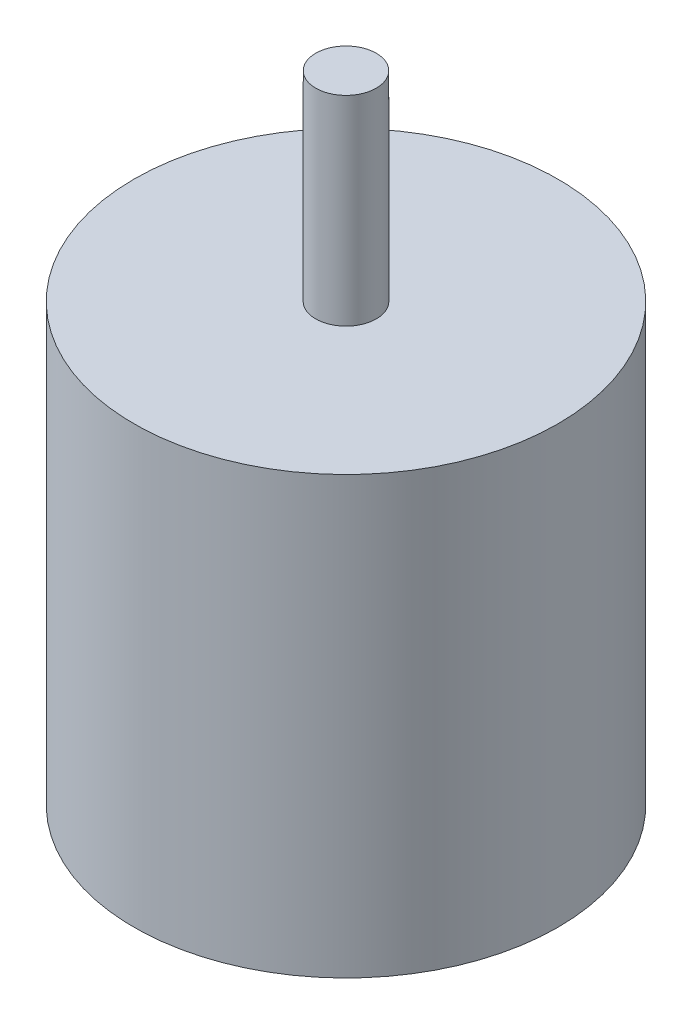
SolidWorks part; units mm, degrees
ref_plane "Front Plane" through (0, 0, 0) normal (0, 0, 1) x (1, 0, 0)
ref_plane "Top Plane" through (0, 0, 0) normal (0, 1, 0) x (1, 0, 0)
ref_plane "Right Plane" through (0, 0, 0) normal (1, 0, 0) x (0, 0, -1)
sketch "Sketch2" plane through (0, 0, 0) normal (0, 0, 1) x (1, 0, 0)
  line L0 (0, 0) -> (0, 21.2167) construction
  line L1 (0, 18) -> (17.5, 18)
  line L2 (0, 18) -> (0, -18)
  line L3 (0, -18) -> (17.5, -18)
  line L4 (17.5, 18) -> (17.5, -18)
  line L5 (0, 18) -> (17.5, -18) construction
  line L6 (0, -18) -> (17.5, 18) construction
  point P0 (8.75, 0)
  point P5 (0, 0)
revolve "Revolve1" add sketch "Sketch2" angle 360 about L2
sketch "Sketch3" plane through (0, 18, 0) normal (0, 1, 0) x (1, 0, 0)
  circle A2 centre (0, 0) radius 2.5
  dimension "D1" = 5
extrude "Boss-Extrude1" add sketch "Sketch3" along normal blind 16.5
sketch "Sketch4" plane through (0, -18, 0) normal (0, -1, 0) x (1, 0, 0)
  line L0 (0, 0) -> (0, 4.7662) construction
  line L1 (0, 0) -> (7.5992, 0) construction
  line L2 (0, 0) -> (-3.9829, 3.9829) construction
  line L3 (0, 0) -> (3.7163, 3.7163) construction
  circle A0 centre (0, 0) radius 9.5 construction
  circle A1 centre (0, 9.5) radius 1.5
  circle A2 centre (0, -9.5) radius 1.5
  circle A4 centre (0, 0) radius 12.5 construction
  circle A5 centre (12.5, 0) radius 1.5
  circle A6 centre (-12.5, 0) radius 1.5
  circle A7 centre (-8.8388, 8.8388) radius 4
  circle A9 centre (8.8388, -8.8388) radius 4
  circle A10 centre (-8.8388, -8.8388) radius 4
  circle A11 centre (8.8388, 8.8388) radius 4
  point P24 (0, 0)
  point P27 (0, 0)
  point P28 (0, 0)
  point P31 (0, 0)
  point P32 (0, 0)
  dimension "D1" = 19
  dimension "D2" = 3
  dimension "D3" = 25
  dimension "D4" = 3
  dimension "D5" = 3
  dimension "D6" = 8
  dimension "D7" = 8
  dimension "D8" = 8
  dimension "D9" = 8
extrude "Cut-Extrude2" cut sketch "Sketch4" against normal blind 5
